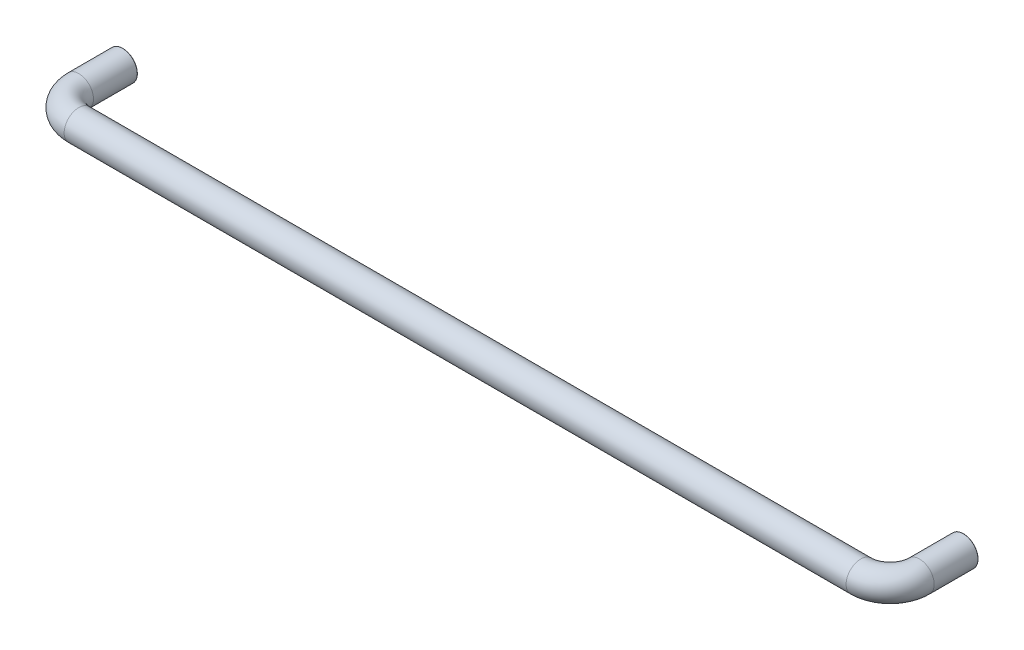
SolidWorks part; units mm, degrees
ref_plane "Front Plane" through (0, 0, 0) normal (0, 0, 1) x (1, 0, 0)
ref_plane "Top Plane" through (0, 0, 0) normal (0, 1, 0) x (1, 0, 0)
ref_plane "Right Plane" through (0, 0, 0) normal (1, 0, 0) x (0, 0, -1)
sketch "Sketch1" plane through (0, 0, 0) normal (0, 1, 0) x (1, 0, 0)
  line L0 (-2705.1, 0) -> (2705.1, 0)
  line L1 (-2908.3, 0) -> (-2705.1, 0) construction
  line L2 (-2908.3, 0) -> (-2908.3, 203.2) construction
  line L3 (-2908.3, 203.2) -> (-2908.3, 508)
  line L4 (0, 0) -> (0, 418.8863) construction
  line L5 (2908.3, 0) -> (2908.3, 203.2) construction
  line L6 (2705.1, 0) -> (2908.3, 0) construction
  line L7 (2908.3, 203.2) -> (2908.3, 508)
  arc A0 (-2908.3, 203.2) -> (-2705.1, 0) centre (-2705.1, 203.2) ccw
  arc A1 (2908.3, 203.2) -> (2705.1, 0) centre (2705.1, 203.2) cw
  point P4 (0, 0)
  dimension "D1" = 406.4
  dimension "D2" = 2908.3
  dimension "D3" = 304.8
ref_plane "Plane1" through (0, 0, -508) normal (0, 0, 1) x (1, 0, 0)
sketch "Sketch2" plane through (0, 0, -508) normal (0, 0, 1) x (1, 0, 0)
  line L0 (-2908.3, 0) -> (-2705.1, 0) construction
  line L1 (-2705.1, 0) -> (-2908.3, 0) construction
  circle A0 centre (-2908.3, 0) radius 101.6
  circle A1 centre (-2908.3, 0) radius 88.9
  dimension "D1" = 203.2
  dimension "D2" = 177.8
sweep "Sweep1" add profiles "Sketch2" path "Sketch1"
fillet "Fillet1" radius 2.54 2 edges at (2806.7, 0, -508) (-2806.7, 0, -508)
